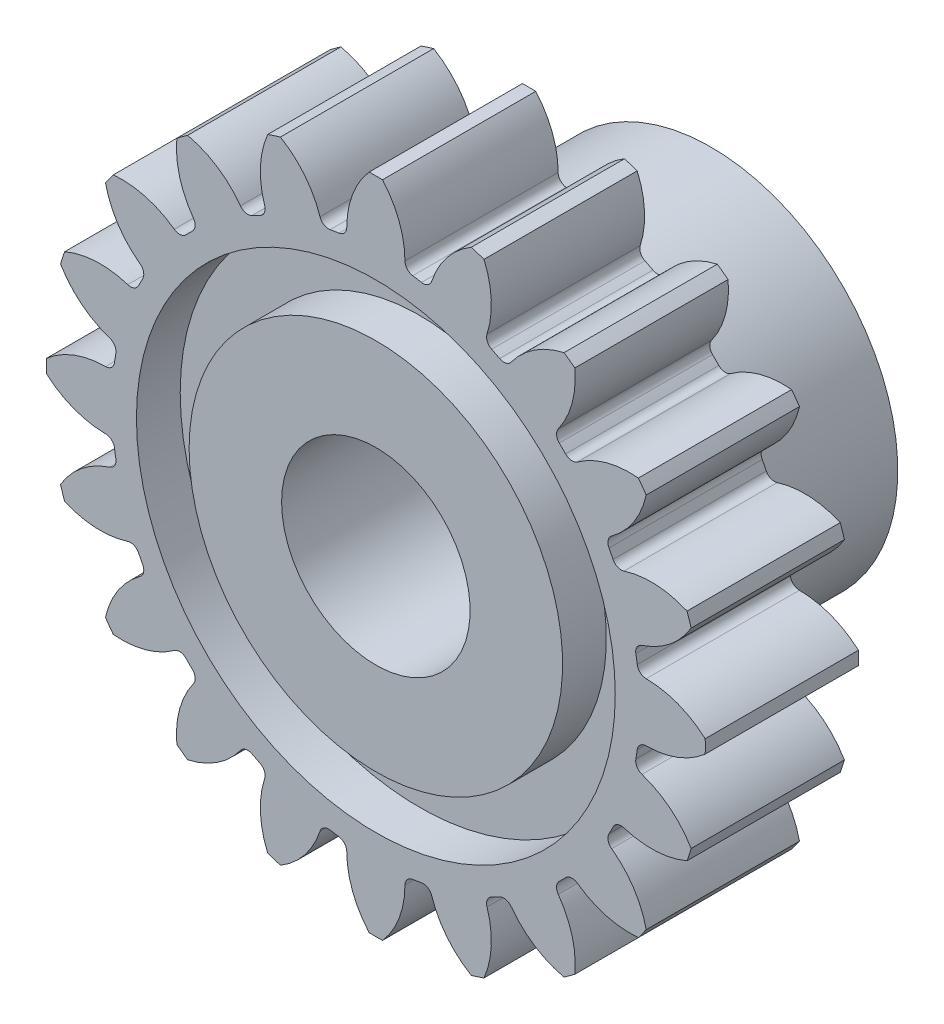
SolidWorks part; units mm, degrees
ref_plane "Front Plane" through (0, 0, 0) normal (0, 0, 1) x (1, 0, 0)
ref_plane "Top Plane" through (0, 0, 0) normal (0, 1, 0) x (1, 0, 0)
ref_plane "Right Plane" through (0, 0, 0) normal (1, 0, 0) x (0, 0, -1)
sketch "Sketch1" plane through (0, 0, 0) normal (1, 0, 0) x (0, 0, -1)
  line L0 (-4.445, 0) -> (-4.445, 8.7376)
  line L1 (-4.445, 8.7376) -> (-0.381, 8.7376)
  line L2 (-0.381, 8.7376) -> (-0.381, 4.953)
  line L3 (-0.381, 4.953) -> (4.445, 4.953)
  line L4 (4.445, 4.953) -> (4.445, 0)
  line L5 (4.445, 0) -> (-4.445, 0) construction
  line L6 (-4.445, 2.5) -> (4.445, 2.5)
  point P9 (-4.445, 6.35)
  dimension "OD" = 17.4752
  dimension "Face Width" = 4.064
  dimension "Hub Width" = 4.826
  dimension "Hub Diameter" = 9.906
  dimension "For Shaft Diameter" = 5
  dimension "Overall Width" = 8.89
  dimension "Under Cut Diameter" = 12.7
sketch "Sketch2" plane through (0, 0, 0) normal (0, 0, 1) x (1, 0, 0)
  line L0 (-1.0101, 6.9276) -> (-0.3513, 8.7376)
  line L1 (-0.3513, 8.7376) -> (0.3513, 8.7376)
  line L2 (0.3513, 8.7376) -> (1.0101, 6.9276)
  line L3 (0, 8.7376) -> (0, 0) construction
  line L4 (0, 0) -> (-1.3669, 8.63) construction
  line L5 (0, 0) -> (1.3669, 8.63) construction
  line L6 (-3.1014, 6.2764) -> (-3.0342, 8.2014)
  line L7 (-3.0342, 8.2014) -> (-2.366, 8.4185)
  line L8 (-2.366, 8.4185) -> (-1.1801, 6.9007)
  line L9 (-2.7001, 8.31) -> (0, 0) construction
  line L11 (-0.3513, 8.7376) -> (0, 8.7376) construction
  line L12 (-0.6284, 7.9763) -> (0.6284, 7.9763) construction
  circle A0 centre (0, 0) radius 8.001 construction
  circle A2 centre (0, 0) radius 8.7376
  circle A3 centre (0, 0) radius 7.0009
  arc A5 (-0.1757, 8.7376) -> (-0.7629, 6.9592) centre (1.605, 7.1634) ccw
  arc A6 (0.7629, 6.9592) -> (0.1757, 8.7376) centre (-1.605, 7.1634) ccw
  arc A7 (-1.4249, 6.8543) -> (-2.533, 8.3642) centre (-3.74, 6.3169) ccw
  arc A8 (-0.6284, 7.9763) -> (0.6284, 7.9763) centre (0, 0) cw
  point P3 (0, 8.001)
  point P5 (2.4724, 7.6094)
  point P9 (4.7029, 6.4729)
  point P10 (6.4729, 4.7029)
  point P11 (7.6094, 2.4724)
  point P12 (8.001, 0)
  point P13 (7.6094, -2.4724)
  point P14 (6.4729, -4.7029)
  point P15 (4.7029, -6.4729)
  point P16 (2.4724, -7.6094)
  point P17 (0, -8.001)
  point P18 (-2.4724, -7.6094)
  point P19 (-4.7029, -6.4729)
  point P20 (-6.4729, -4.7029)
  point P21 (-7.6094, -2.4724)
  point P22 (-8.001, 0)
  point P23 (-7.6094, 2.4724)
  point P24 (-6.4729, 4.7029)
  point P25 (-4.7029, 6.4729)
  point P26 (-2.4724, 7.6094)
  point P31 (0, 0)
  dimension "Gear Pitch Diameter" = 16.002
  dimension "Pressure Angle" = 20
  dimension "Addendum" = 0.7366
  dimension "Dedendum" = 1.0001
  dimension "D1" = 18
  dimension "D2" = 1.2568
  dimension "Number of Teeth" = 20
sketch "Sketch3" plane through (0, 0, 0) normal (1, 0, 0) x (0, 0, -1)
  line L0 (-4.445, 8.7376) -> (-0.381, 8.7376) construction
  line L1 (4.445, 4.953) -> (4.445, 0) construction
  line L2 (-0.381, 4.953) -> (4.445, 4.953) construction
  line L3 (-0.381, 8.7376) -> (-0.381, 4.953) construction
  line L4 (-4.445, 0) -> (-4.445, 8.7376) construction
  line L5 (-4.445, 2.5) -> (4.445, 2.5) construction
  line L6 (-4.445, 8.7376) -> (-0.381, 8.7376)
  line L7 (4.445, 4.953) -> (4.445, 2.5)
  line L8 (-4.445, 4.953) -> (-3.2839, 4.953)
  line L9 (-0.381, 8.7376) -> (-0.381, 6.35)
  line L10 (-4.445, 2.5) -> (-4.445, 4.953)
  line L11 (-4.445, 2.5) -> (4.445, 2.5)
  line L12 (-4.445, 6.35) -> (-3.2839, 6.35)
  line L13 (-3.2839, 6.35) -> (-3.2839, 4.953)
  line L14 (-0.381, 6.35) -> (-1.5421, 6.35)
  line L15 (-1.5421, 6.35) -> (-1.5421, 4.953)
  line L16 (-1.5421, 4.953) -> (4.445, 4.953)
  line L17 (-4.445, 6.35) -> (-4.445, 8.7376)
  dimension "D1" = 1.1611
revolve "Revolve1" add sketch "Sketch3" angle 360 about L5
sketch "Sketch4" plane through (0, 0, 4.445) normal (0, 0, 1) x (1, 0, 0)
  arc A1 (-0.1757, 8.7376) -> (-0.7629, 6.9592) centre (1.605, 7.1634) ccw construction
  arc A2 (-1.4249, 6.8543) -> (-2.533, 8.3642) centre (-3.74, 6.3169) ccw construction
  arc A3 (-0.1772, 8.7358) -> (-0.7717, 7.1693) centre (1.605, 7.1634) ccw
  arc A4 (-1.4815, 7.0569) -> (-2.5309, 8.363) centre (-3.74, 6.3169) ccw
  circle A5 centre (0, 0) radius 8.7376 construction
  arc A6 (-0.1772, 8.7358) -> (-2.5309, 8.363) centre (0, 0) ccw
  circle A7 centre (0, 0) radius 7.0009 construction
  arc A8 (-0.9782, 6.9322) -> (-1.2118, 6.8952) centre (0, 0) ccw
  arc A9 (-1.4815, 7.0569) -> (-1.2118, 6.8952) centre (-1.2534, 7.1316) ccw
  arc A10 (-0.9782, 6.9322) -> (-0.7717, 7.1693) centre (-1.0118, 7.1699) ccw
  dimension "D1" = 0.24
extrude "Cut-Extrude1" cut sketch "Sketch4" against normal through all both and the other way through all
pattern_circular "CirPattern1" count 20 over 360 about axis through (0, 0, 0) along (0, 0, 1) of "Cut-Extrude1"
equation "\"Dedendum@Sketch2\" = 1.25 /  ( \"Number of Teeth@Sketch2\" / \"Gear Pitch Diameter@Sketch2\" ) "
equation "\"D1@Sketch2\"=360/\"Number of Teeth@Sketch2\""
equation "\"D1@Sketch4\"=.3/(\"Number of Teeth@Sketch2\"/\"Gear Pitch Diameter@Sketch2\")"
equation "\"D1@CirPattern1\"=\"Number of Teeth@Sketch2\""
equation "\"D2@Sketch2\"=1.5708/(\"Number of Teeth@Sketch2\"/\"Gear Pitch Diameter@Sketch2\")"
equation "\"D1@Sketch3\"=\"Face Width@Sketch1\"/3.5"
